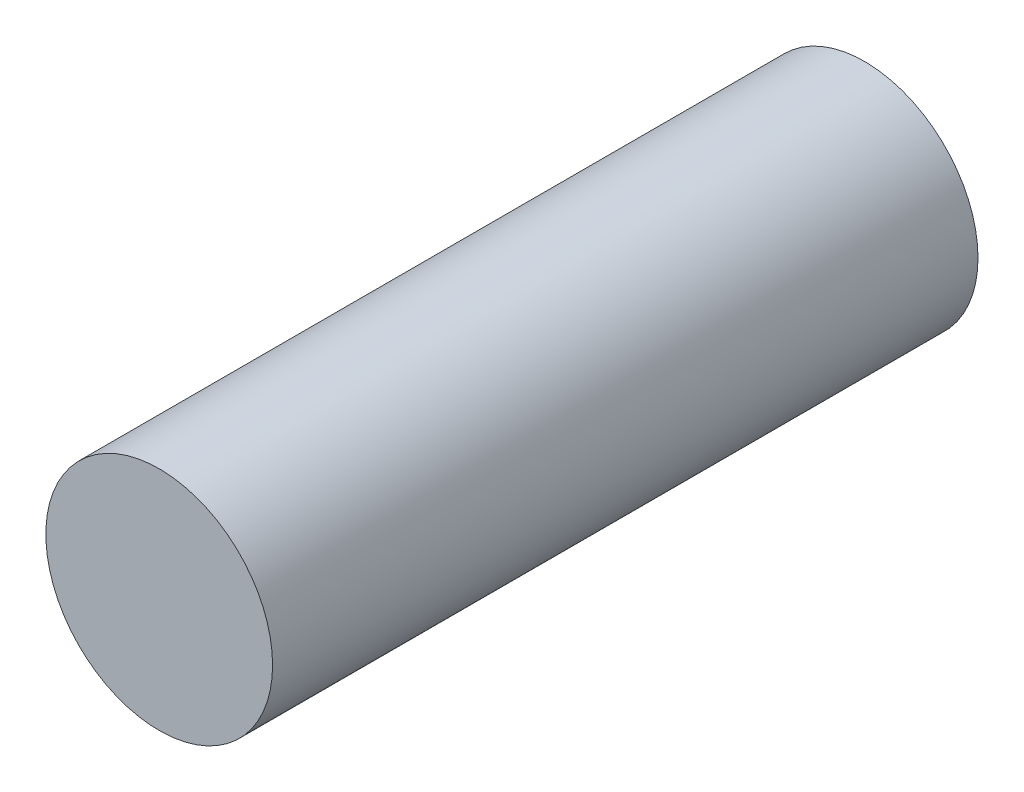
SolidWorks part; units mm, degrees
ref_plane "Alzado" through (0, 0, 0) normal (0, 0, 1) x (1, 0, 0)
ref_plane "Planta" through (0, 0, 0) normal (0, 1, 0) x (1, 0, 0)
ref_plane "Vista lateral" through (0, 0, 0) normal (1, 0, 0) x (0, 0, -1)
sketch "Croquis1" plane through (0, 0, 0) normal (0, 0, 1) x (1, 0, 0)
  circle A0 centre (0, 0) radius 9
  dimension "D1" = 18
extrude "Saliente-Extruir1" add sketch "Croquis1" along normal blind 56
